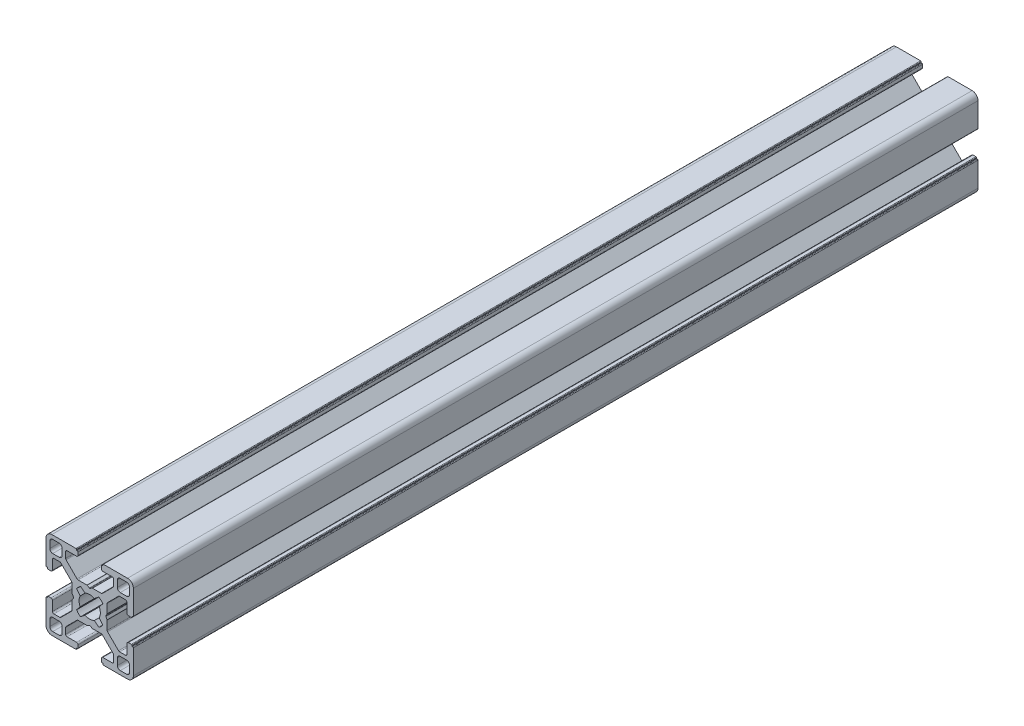
SolidWorks part; units mm, degrees
ref_plane "Ebene vorne" through (0, 0, 0) normal (0, 0, 1) x (1, 0, 0)
ref_plane "Ebene oben" through (0, 0, 0) normal (0, 1, 0) x (1, 0, 0)
ref_plane "Ebene rechts" through (0, 0, 0) normal (1, 0, 0) x (0, 0, -1)
ref_plane "Ebene1" through (0, 0, 1000) normal (0, 0, 1) x (1, 0, 0)
sketch "Skizze1" plane through (0, 0, 1000) normal (0, 0, 1) x (1, 0, 0)
  line L0 (8, -5.5) -> (5.8, -5.5)
  line L1 (4.8, -4.5) -> (4.8, -2.3)
  line L2 (5.8, -1.3) -> (8, -1.3)
  line L3 (9, -2.3) -> (9, -4.5)
  line L4 (-15.2, -5.5) -> (-17.4, -5.5)
  line L5 (-18.4, -4.5) -> (-18.4, -2.3)
  line L6 (-17.4, -1.3) -> (-15.2, -1.3)
  line L7 (-14.2, -2.3) -> (-14.2, -4.5)
  line L8 (-17.4, -24.5) -> (-15.2, -24.5)
  line L9 (-14.2, -25.5) -> (-14.2, -27.7)
  line L10 (-15.2, -28.7) -> (-17.4, -28.7)
  line L11 (-18.4, -27.7) -> (-18.4, -25.5)
  line L12 (5.8, -24.5) -> (8, -24.5)
  line L13 (9, -25.5) -> (9, -27.7)
  line L14 (8, -28.7) -> (5.8, -28.7)
  line L15 (4.8, -27.7) -> (4.8, -25.5)
  line L16 (-7.8359, -10.4816) -> (-6.3001, -11.7194)
  line L17 (-3.0999, -11.7194) -> (-1.5641, -10.4816)
  line L18 (-0.1947, -11.8453) -> (-1.4194, -13.3999)
  line L19 (-1.4194, -16.6001) -> (-0.1947, -18.1547)
  line L20 (-1.5641, -19.5184) -> (-3.0999, -18.2806)
  line L21 (-6.3001, -18.2806) -> (-7.8359, -19.5184)
  line L22 (-9.2053, -18.1547) -> (-7.9806, -16.6001)
  line L23 (-7.9806, -13.3999) -> (-9.2053, -11.8453)
  line L24 (9.8, -10.5) -> (10.1, -10.5)
  line L25 (10.3, -10.3) -> (10.3, -2)
  line L26 (8.3, 0) -> (0, 0)
  line L27 (-0.2, -0.2) -> (-0.2, -0.5)
  line L28 (-0.2, -0.5) -> (-0.5, -0.5)
  line L29 (-0.7, -0.7) -> (-0.7, -1.7)
  line L30 (-0.2, -2.2) -> (3.05, -2.2)
  line L31 (3.55, -2.7) -> (3.55, -4.7431)
  line L32 (3.4037, -5.0964) -> (-0.3491, -8.8534)
  line L33 (-0.7028, -9) -> (-3.7468, -9)
  line L34 (-3.8462, -9.0264) -> (-4.6006, -9.4583)
  line L35 (-4.7994, -9.4583) -> (-5.5538, -9.0264)
  line L36 (-5.6532, -9) -> (-8.6972, -9)
  line L37 (-9.0509, -8.8534) -> (-12.8037, -5.0964)
  line L38 (-12.95, -4.7431) -> (-12.95, -2.7)
  line L39 (-12.45, -2.2) -> (-9.2, -2.2)
  line L40 (-8.7, -1.7) -> (-8.7, -0.7)
  line L41 (-8.9, -0.5) -> (-9.2, -0.5)
  line L42 (-9.2, -0.5) -> (-9.2, -0.2)
  line L43 (-9.4, 0) -> (-17.7, 0)
  line L44 (-19.7, -2) -> (-19.7, -10.3)
  line L45 (-19.5, -10.5) -> (-19.2, -10.5)
  line L46 (-19.2, -10.5) -> (-19.2, -10.8)
  line L47 (-19, -11) -> (-18, -11)
  line L48 (-17.5, -10.5) -> (-17.5, -7.25)
  line L49 (-17, -6.75) -> (-14.9569, -6.75)
  line L50 (-14.6036, -6.8963) -> (-10.8466, -10.6491)
  line L51 (-10.7, -11.0028) -> (-10.7, -14.0468)
  line L52 (-10.6736, -14.1462) -> (-10.2417, -14.9006)
  line L53 (-10.2417, -15.0994) -> (-10.6736, -15.8538)
  line L54 (-10.7, -15.9532) -> (-10.7, -18.9972)
  line L55 (-10.8466, -19.3509) -> (-14.6036, -23.1037)
  line L56 (-14.9569, -23.25) -> (-17, -23.25)
  line L57 (-17.5, -22.75) -> (-17.5, -19.5)
  line L58 (-18, -19) -> (-19, -19)
  line L59 (-19.2, -19.2) -> (-19.2, -19.5)
  line L60 (-19.2, -19.5) -> (-19.5, -19.5)
  line L61 (-19.7, -19.7) -> (-19.7, -28)
  line L62 (-17.7, -30) -> (-9.4, -30)
  line L63 (-9.2, -29.8) -> (-9.2, -29.5)
  line L64 (-9.2, -29.5) -> (-8.9, -29.5)
  line L65 (-8.7, -29.3) -> (-8.7, -28.3)
  line L66 (-9.2, -27.8) -> (-12.45, -27.8)
  line L67 (-12.95, -27.3) -> (-12.95, -25.2569)
  line L68 (-12.8037, -24.9036) -> (-9.0509, -21.1466)
  line L69 (-8.6972, -21) -> (-5.6532, -21)
  line L70 (-5.5538, -20.9736) -> (-4.7994, -20.5417)
  line L71 (-4.6006, -20.5417) -> (-3.8462, -20.9736)
  line L72 (-3.7468, -21) -> (-0.7028, -21)
  line L73 (-0.3491, -21.1466) -> (3.4037, -24.9036)
  line L74 (3.55, -25.2569) -> (3.55, -27.3)
  line L75 (3.05, -27.8) -> (-0.2, -27.8)
  line L76 (-0.7, -28.3) -> (-0.7, -29.3)
  line L77 (-0.5, -29.5) -> (-0.2, -29.5)
  line L78 (-0.2, -29.5) -> (-0.2, -29.8)
  line L79 (0, -30) -> (8.3, -30)
  line L80 (10.3, -28) -> (10.3, -19.7)
  line L81 (10.1, -19.5) -> (9.8, -19.5)
  line L82 (9.8, -19.5) -> (9.8, -19.2)
  line L83 (9.6, -19) -> (8.6, -19)
  line L84 (8.1, -19.5) -> (8.1, -22.75)
  line L85 (7.6, -23.25) -> (5.5569, -23.25)
  line L86 (5.2036, -23.1037) -> (1.4466, -19.3509)
  line L87 (1.3, -18.9972) -> (1.3, -15.9532)
  line L88 (1.2736, -15.8538) -> (0.8417, -15.0994)
  line L89 (0.8417, -14.9006) -> (1.2736, -14.1462)
  line L90 (1.3, -14.0468) -> (1.3, -11.0028)
  line L91 (1.4466, -10.6491) -> (5.2036, -6.8963)
  line L92 (5.5569, -6.75) -> (7.6, -6.75)
  line L93 (8.1, -7.25) -> (8.1, -10.5)
  line L94 (8.6, -11) -> (9.6, -11)
  line L95 (9.8, -10.8) -> (9.8, -10.5)
  arc A0 (9, -4.5) -> (8, -5.5) centre (8, -4.5) cw
  arc A1 (5.8, -5.5) -> (4.8, -4.5) centre (5.8, -4.5) cw
  arc A2 (4.8, -2.3) -> (5.8, -1.3) centre (5.8, -2.3) cw
  arc A3 (8, -1.3) -> (9, -2.3) centre (8, -2.3) cw
  arc A4 (-14.2, -4.5) -> (-15.2, -5.5) centre (-15.2, -4.5) cw
  arc A5 (-17.4, -5.5) -> (-18.4, -4.5) centre (-17.4, -4.5) cw
  arc A6 (-18.4, -2.3) -> (-17.4, -1.3) centre (-17.4, -2.3) cw
  arc A7 (-15.2, -1.3) -> (-14.2, -2.3) centre (-15.2, -2.3) cw
  arc A8 (-18.4, -25.5) -> (-17.4, -24.5) centre (-17.4, -25.5) cw
  arc A9 (-15.2, -24.5) -> (-14.2, -25.5) centre (-15.2, -25.5) cw
  arc A10 (-14.2, -27.7) -> (-15.2, -28.7) centre (-15.2, -27.7) cw
  arc A11 (-17.4, -28.7) -> (-18.4, -27.7) centre (-17.4, -27.7) cw
  arc A12 (4.8, -25.5) -> (5.8, -24.5) centre (5.8, -25.5) cw
  arc A13 (8, -24.5) -> (9, -25.5) centre (8, -25.5) cw
  arc A14 (9, -27.7) -> (8, -28.7) centre (8, -27.7) cw
  arc A15 (5.8, -28.7) -> (4.8, -27.7) centre (5.8, -27.7) cw
  arc A16 (-9.2053, -11.8453) -> (-7.8359, -10.4816) centre (-4.7, -15) cw
  arc A17 (-6.3001, -11.7194) -> (-3.0999, -11.7194) centre (-4.7, -15) cw
  arc A18 (-1.5641, -10.4816) -> (-0.1947, -11.8453) centre (-4.7, -15) cw
  arc A19 (-1.4194, -13.3999) -> (-1.4194, -16.6001) centre (-4.7, -15) cw
  arc A20 (-0.1947, -18.1547) -> (-1.5641, -19.5184) centre (-4.7, -15) cw
  arc A21 (-3.0999, -18.2806) -> (-6.3001, -18.2806) centre (-4.7, -15) cw
  arc A22 (-7.8359, -19.5184) -> (-9.2053, -18.1547) centre (-4.7, -15) cw
  arc A23 (-7.9806, -16.6001) -> (-7.9806, -13.3999) centre (-4.7, -15) cw
  arc A24 (10.1, -10.5) -> (10.3, -10.3) centre (10.1, -10.3) ccw
  arc A25 (10.3, -2) -> (8.3, 0) centre (8.3, -2) ccw
  arc A26 (0, 0) -> (-0.2, -0.2) centre (0, -0.2) ccw
  arc A27 (-0.5, -0.5) -> (-0.7, -0.7) centre (-0.5, -0.7) ccw
  arc A28 (-0.7, -1.7) -> (-0.2, -2.2) centre (-0.2, -1.7) ccw
  arc A29 (3.05, -2.2) -> (3.55, -2.7) centre (3.05, -2.7) cw
  arc A30 (3.55, -4.7431) -> (3.4037, -5.0964) centre (3.05, -4.7431) cw
  arc A31 (-0.3491, -8.8534) -> (-0.7028, -9) centre (-0.7028, -8.5) cw
  arc A32 (-3.7468, -9) -> (-3.8462, -9.0264) centre (-3.7468, -9.2) ccw
  arc A33 (-4.6006, -9.4583) -> (-4.7994, -9.4583) centre (-4.7, -9.2847) cw
  arc A34 (-5.5538, -9.0264) -> (-5.6532, -9) centre (-5.6532, -9.2) ccw
  arc A35 (-8.6972, -9) -> (-9.0509, -8.8534) centre (-8.6972, -8.5) cw
  arc A36 (-12.8037, -5.0964) -> (-12.95, -4.7431) centre (-12.45, -4.7431) cw
  arc A37 (-12.95, -2.7) -> (-12.45, -2.2) centre (-12.45, -2.7) cw
  arc A38 (-9.2, -2.2) -> (-8.7, -1.7) centre (-9.2, -1.7) ccw
  arc A39 (-8.7, -0.7) -> (-8.9, -0.5) centre (-8.9, -0.7) ccw
  arc A40 (-9.2, -0.2) -> (-9.4, 0) centre (-9.4, -0.2) ccw
  arc A41 (-17.7, 0) -> (-19.7, -2) centre (-17.7, -2) ccw
  arc A42 (-19.7, -10.3) -> (-19.5, -10.5) centre (-19.5, -10.3) ccw
  arc A43 (-19.2, -10.8) -> (-19, -11) centre (-19, -10.8) ccw
  arc A44 (-18, -11) -> (-17.5, -10.5) centre (-18, -10.5) ccw
  arc A45 (-17.5, -7.25) -> (-17, -6.75) centre (-17, -7.25) cw
  arc A46 (-14.9569, -6.75) -> (-14.6036, -6.8963) centre (-14.9569, -7.25) cw
  arc A47 (-10.8466, -10.6491) -> (-10.7, -11.0028) centre (-11.2, -11.0028) cw
  arc A48 (-10.7, -14.0468) -> (-10.6736, -14.1462) centre (-10.5, -14.0468) ccw
  arc A49 (-10.2417, -14.9006) -> (-10.2417, -15.0994) centre (-10.4153, -15) cw
  arc A50 (-10.6736, -15.8538) -> (-10.7, -15.9532) centre (-10.5, -15.9532) ccw
  arc A51 (-10.7, -18.9972) -> (-10.8466, -19.3509) centre (-11.2, -18.9972) cw
  arc A52 (-14.6036, -23.1037) -> (-14.9569, -23.25) centre (-14.9569, -22.75) cw
  arc A53 (-17, -23.25) -> (-17.5, -22.75) centre (-17, -22.75) cw
  arc A54 (-17.5, -19.5) -> (-18, -19) centre (-18, -19.5) ccw
  arc A55 (-19, -19) -> (-19.2, -19.2) centre (-19, -19.2) ccw
  arc A56 (-19.5, -19.5) -> (-19.7, -19.7) centre (-19.5, -19.7) ccw
  arc A57 (-19.7, -28) -> (-17.7, -30) centre (-17.7, -28) ccw
  arc A58 (-9.4, -30) -> (-9.2, -29.8) centre (-9.4, -29.8) ccw
  arc A59 (-8.9, -29.5) -> (-8.7, -29.3) centre (-8.9, -29.3) ccw
  arc A60 (-8.7, -28.3) -> (-9.2, -27.8) centre (-9.2, -28.3) ccw
  arc A61 (-12.45, -27.8) -> (-12.95, -27.3) centre (-12.45, -27.3) cw
  arc A62 (-12.95, -25.2569) -> (-12.8037, -24.9036) centre (-12.45, -25.2569) cw
  arc A63 (-9.0509, -21.1466) -> (-8.6972, -21) centre (-8.6972, -21.5) cw
  arc A64 (-5.6532, -21) -> (-5.5538, -20.9736) centre (-5.6532, -20.8) ccw
  arc A65 (-4.7994, -20.5417) -> (-4.6006, -20.5417) centre (-4.7, -20.7153) cw
  arc A66 (-3.8462, -20.9736) -> (-3.7468, -21) centre (-3.7468, -20.8) ccw
  arc A67 (-0.7028, -21) -> (-0.3491, -21.1466) centre (-0.7028, -21.5) cw
  arc A68 (3.4037, -24.9036) -> (3.55, -25.2569) centre (3.05, -25.2569) cw
  arc A69 (3.55, -27.3) -> (3.05, -27.8) centre (3.05, -27.3) cw
  arc A70 (-0.2, -27.8) -> (-0.7, -28.3) centre (-0.2, -28.3) ccw
  arc A71 (-0.7, -29.3) -> (-0.5, -29.5) centre (-0.5, -29.3) ccw
  arc A72 (-0.2, -29.8) -> (0, -30) centre (0, -29.8) ccw
  arc A73 (8.3, -30) -> (10.3, -28) centre (8.3, -28) ccw
  arc A74 (10.3, -19.7) -> (10.1, -19.5) centre (10.1, -19.7) ccw
  arc A75 (9.8, -19.2) -> (9.6, -19) centre (9.6, -19.2) ccw
  arc A76 (8.6, -19) -> (8.1, -19.5) centre (8.6, -19.5) ccw
  arc A77 (8.1, -22.75) -> (7.6, -23.25) centre (7.6, -22.75) cw
  arc A78 (5.5569, -23.25) -> (5.2036, -23.1037) centre (5.5569, -22.75) cw
  arc A79 (1.4466, -19.3509) -> (1.3, -18.9972) centre (1.8, -18.9972) cw
  arc A80 (1.3, -15.9532) -> (1.2736, -15.8538) centre (1.1, -15.9532) ccw
  arc A81 (0.8417, -15.0994) -> (0.8417, -14.9006) centre (1.0153, -15) cw
  arc A82 (1.2736, -14.1462) -> (1.3, -14.0468) centre (1.1, -14.0468) ccw
  arc A83 (1.3, -11.0028) -> (1.4466, -10.6491) centre (1.8, -11.0028) cw
  arc A84 (5.2036, -6.8963) -> (5.5569, -6.75) centre (5.5569, -7.25) cw
  arc A85 (7.6, -6.75) -> (8.1, -7.25) centre (7.6, -7.25) cw
  arc A86 (8.1, -10.5) -> (8.6, -11) centre (8.6, -10.5) ccw
  arc A87 (9.6, -11) -> (9.8, -10.8) centre (9.6, -10.8) ccw
extrude "Aufsatz-Linear austragen1" add sketch "Skizze1" against normal blind 290
